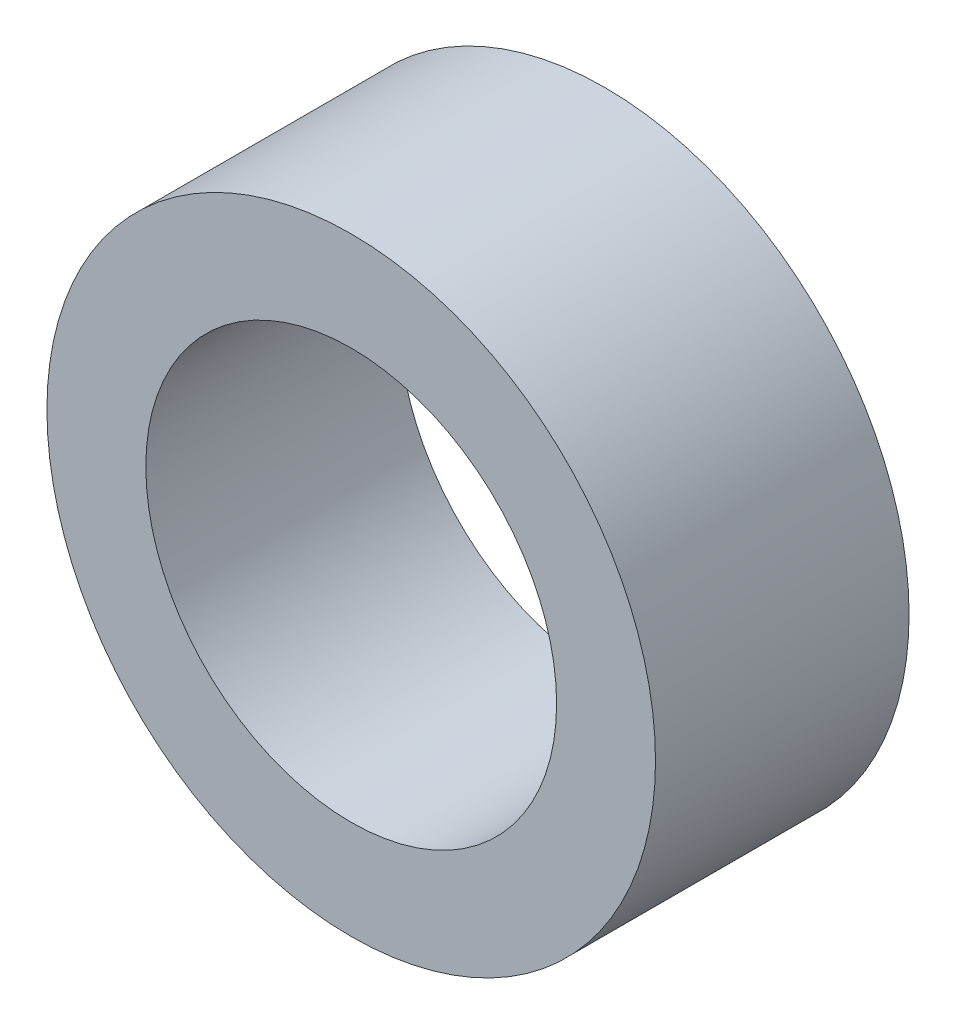
SolidWorks part; units mm, degrees
ref_plane "Front Plane" through (0, 0, 0) normal (0, 0, 1) x (1, 0, 0)
ref_plane "Top Plane" through (0, 0, 0) normal (0, 1, 0) x (1, 0, 0)
ref_plane "Right Plane" through (0, 0, 0) normal (1, 0, 0) x (0, 0, -1)
sketch "Sketch1" plane through (0, 0, 0) normal (0, 0, 1) x (1, 0, 0)
  circle A0 centre (0, 0) radius 4.05
  circle A1 centre (0, 0) radius 6
  dimension "D1" = 8.1
  dimension "D2" = 12
extrude "Boss-Extrude1" add sketch "Sketch1" along normal blind 5
